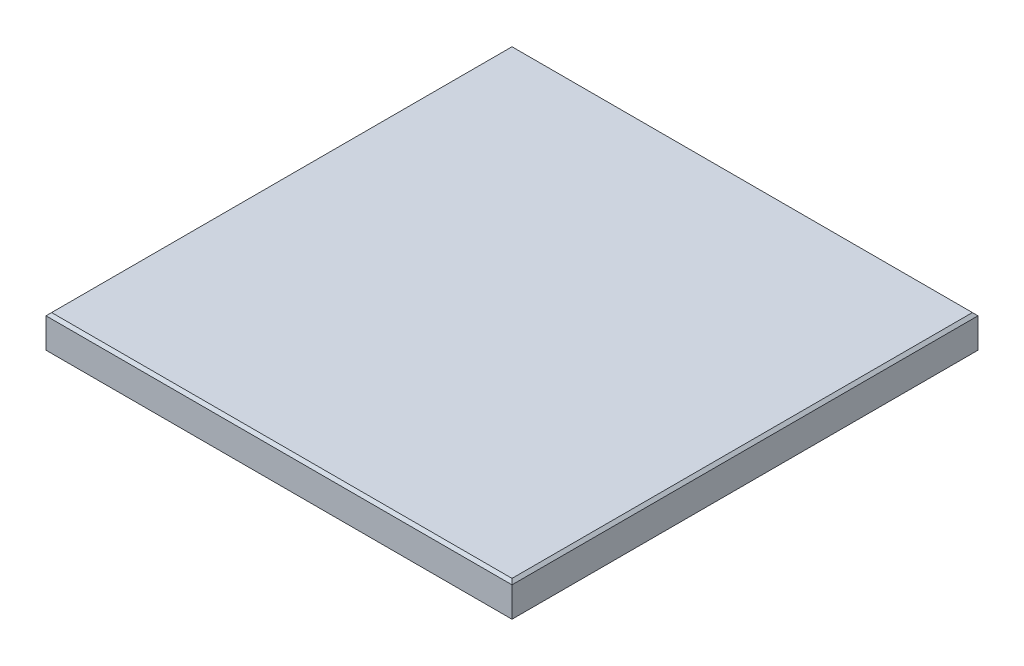
SolidWorks part; units mm, degrees
ref_plane "Front Plane" through (0, 0, 0) normal (0, 0, 1) x (1, 0, 0)
ref_plane "Top Plane" through (0, 0, 0) normal (0, 1, 0) x (1, 0, 0)
ref_plane "Right Plane" through (0, 0, 0) normal (1, 0, 0) x (0, 0, -1)
sketch "Sketch1" plane through (0, 0, 0) normal (0, 1, 0) x (1, 0, 0)
  line L1 (-63.5, -63.5) -> (63.5, -63.5)
  line L2 (-63.5, -63.5) -> (-63.5, 63.5)
  line L3 (-63.5, 63.5) -> (63.5, 63.5)
  line L4 (63.5, -63.5) -> (63.5, 63.5)
  line L5 (-63.5, -63.5) -> (63.5, 63.5) construction
  line L6 (-63.5, 63.5) -> (63.5, -63.5) construction
  point P0 (0, 0)
  dimension "D1" = 127
  dimension "D2" = 127
extrude "Boss-Extrude1" add sketch "Sketch1" along normal blind 15.24
sketch "Sketch2" plane through (0, 0, 0) normal (0, -1, 0) x (1, 0, 0)
  line L11 (-63.5, -63.5) -> (63.5, -63.5)
  line L12 (-63.5, -63.5) -> (-63.5, 63.5)
  line L13 (-63.5, 63.5) -> (63.5, 63.5)
  line L14 (50.165, -50.165) -> (50.165, 50.165)
  line L15 (-50.165, -50.165) -> (50.165, -50.165)
  line L16 (-50.165, 50.165) -> (-50.165, -50.165)
  line L17 (50.165, 50.165) -> (-50.165, 50.165)
  line L18 (50.165, -50.165) -> (50.165, 50.165)
  line L19 (-50.165, -50.165) -> (50.165, -50.165)
  line L20 (-50.165, 50.165) -> (-50.165, -50.165)
  line L21 (50.165, 50.165) -> (-50.165, 50.165)
  line L22 (63.5, -63.5) -> (63.5, 63.5)
  line L23 (-63.5, -63.5) -> (63.5, 63.5) construction
  line L24 (-63.5, 63.5) -> (63.5, -63.5) construction
  point P0 (0, 0)
  dimension "D1" = 13.335
extrude "Cut-Extrude1" cut sketch "Sketch2" against normal blind 6.35
fillet "Fillet1" radius 0.762 4 edges at (-50.165, 3.175, -50.165) (50.165, 3.175, -50.165) (50.165, 3.175, 50.165) (-50.165, 3.175, 50.165)
fillet "Fillet2" [suppressed] radius 0.762
chamfer "Chamfer1" distance 0.762 angle 45 4 edges at (0, 15.24, -63.5) (63.5, 15.24, 0) (0, 15.24, 63.5) (-63.5, 15.24, 0)
